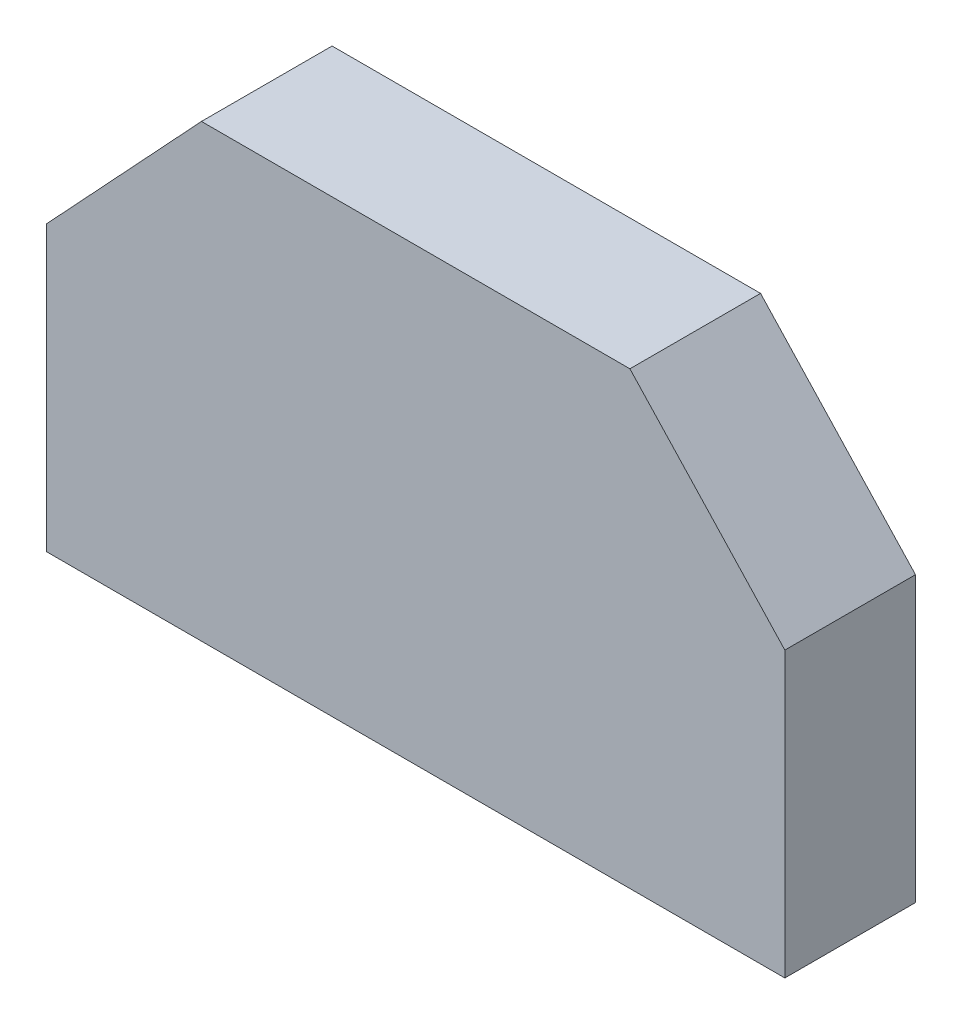
SolidWorks part; units mm, degrees
ref_plane "Front Plane" through (0, 0, 0) normal (0, 0, 1) x (1, 0, 0)
ref_plane "Top Plane" through (0, 0, 0) normal (0, 1, 0) x (1, 0, 0)
ref_plane "Right Plane" through (0, 0, 0) normal (1, 0, 0) x (0, 0, -1)
sketch "Sketch1" plane through (0, 0, 0) normal (0, 0, 1) x (1, 0, 0)
  line L0 (-165.1, 0) -> (165.1, 0)
  line L1 (-165.1, 0) -> (-165.1, 127)
  line L2 (-165.1, 127) -> (-95.809, 201.3055)
  line L3 (-95.809, 201.3055) -> (95.809, 201.3055)
  line L4 (0, 263.0824) -> (0, 69.284) construction
  line L5 (165.1, 0) -> (165.1, 127)
  line L6 (165.1, 127) -> (95.809, 201.3055)
  point P3 (0, 0)
  point P11 (0, 201.3055)
  dimension "D1" = 330.2
  dimension "D2" = 127
  dimension "D3" = 101.6
  dimension "D4" = 137
extrude "Boss-Extrude1" add sketch "Sketch1" along normal mid plane 58.42
